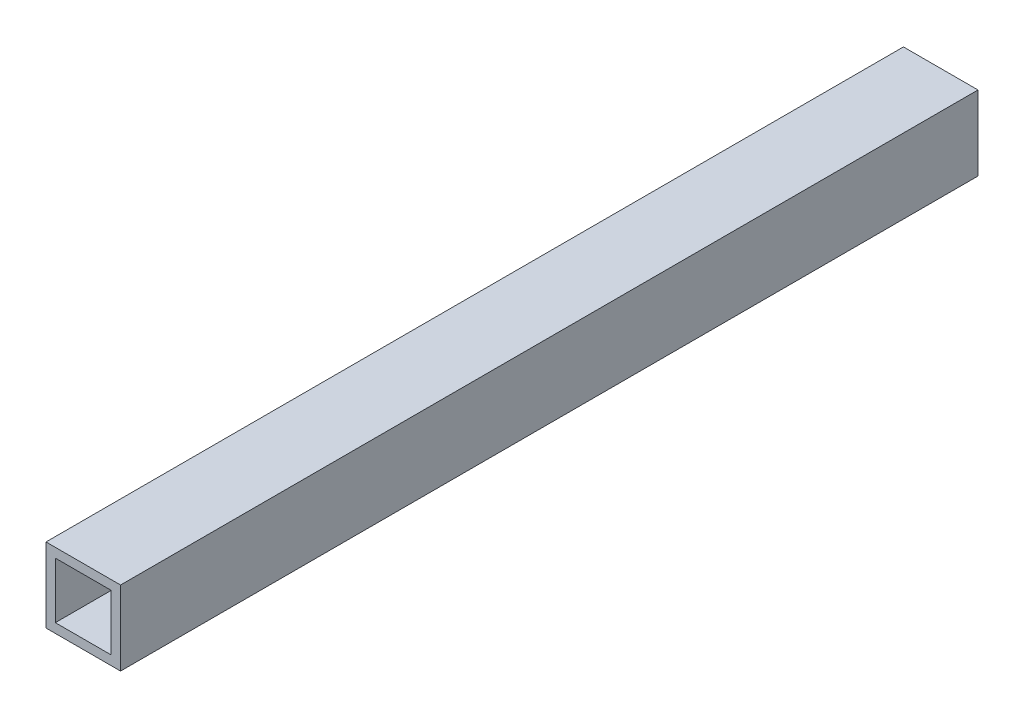
SolidWorks part; units mm, degrees
ref_plane "Front Plane" through (0, 0, 0) normal (0, 0, 1) x (1, 0, 0)
ref_plane "Top Plane" through (0, 0, 0) normal (0, 1, 0) x (1, 0, 0)
ref_plane "Right Plane" through (0, 0, 0) normal (1, 0, 0) x (0, 0, -1)
sketch "Sketch1" plane through (0, 0, 0) normal (0, 0, 1) x (1, 0, 0)
  line L0 (12.7, 0) -> (9.525, 0) construction
  line L1 (-12.7, 0) -> (12.7, 0) construction
  line L2 (0, 12.7) -> (0, -12.7)
  point P7 (0, 0)
sketch "Sketch2" plane through (0, 0, 0) normal (1, 0, 0) x (0, 0, -1)
  line L0 (146.05, 0) -> (-146.05, 0)
  point P4 (0, 0)
  dimension "Length" = 292.1
sketch "Sketch3" plane through (0, 0, 0) normal (0, 0, 1) x (1, 0, 0)
  line L0 (-12.7, 0) -> (12.7, 0) construction
  line L5 (12.7, -12.7) -> (-12.7, -12.7)
  line L6 (12.7, -12.7) -> (12.7, 12.7)
  line L11 (12.7, 12.7) -> (-12.7, 12.7)
  line L12 (-12.7, -12.7) -> (-12.7, 12.7)
  line L14 (12.7, -12.7) -> (-12.7, 12.7) construction
  line L15 (12.7, 12.7) -> (-12.7, -12.7) construction
  line L16 (9.525, -9.525) -> (-9.525, -9.525)
  line L17 (9.525, -9.525) -> (9.525, 9.525)
  line L18 (9.525, 9.525) -> (-9.525, 9.525)
  line L19 (-9.525, -9.525) -> (-9.525, 9.525)
  line L20 (9.525, -9.525) -> (-9.525, 9.525) construction
  line L21 (9.525, 9.525) -> (-9.525, -9.525) construction
  point P0 (0, 0)
  point P5 (0, 0)
  point P13 (9.525, -12.7)
  dimension "D1" = 3.175
  dimension "D3" = 25.4
  dimension "D4" = 25.4
extrude "Boss-Extrude1" add sketch "Sketch3" along normal up to vertex (146.05 mm away) and the other way up to vertex (146.05 mm away) up to point (0, 0, 146.05) other way up to point (0, 0, -146.05)
sketch "Sketch5" plane through (0, 0, 0) normal (1, 0, 0) x (0, 0, -1)
  line L0 (-146.05, 0) -> (146.05, 0) construction
  line L3 (-146.05, -12.7) -> (-146.05, 12.7) construction
  line L4 (146.05, -12.7) -> (146.05, 12.7) construction
  point P6 (-117.475, 0)
  point P7 (-107.95, 0)
  point P8 (107.95, 0)
  point P10 (117.475, 0)
  dimension "D1" = 28.575
  dimension "D2" = 38.1
  dimension "D3" = 28.575
  dimension "D4" = 38.1
equation "\"D1@Sketch3\"=\"Wall thickness@Sketch1\""
equation "\"D1@Sketch5\"=\"Width@Sketch1\"*1.125"
equation "\"D2@Sketch5\"=\"Width@Sketch1\"*1.5"
equation "\"D3@Sketch5\"=\"D1@Sketch5\""
equation "\"D4@Sketch5\"=\"D2@Sketch5\""
equation "\"D2@Sketch3\"=\"Wall Thickness@Sketch1\""
